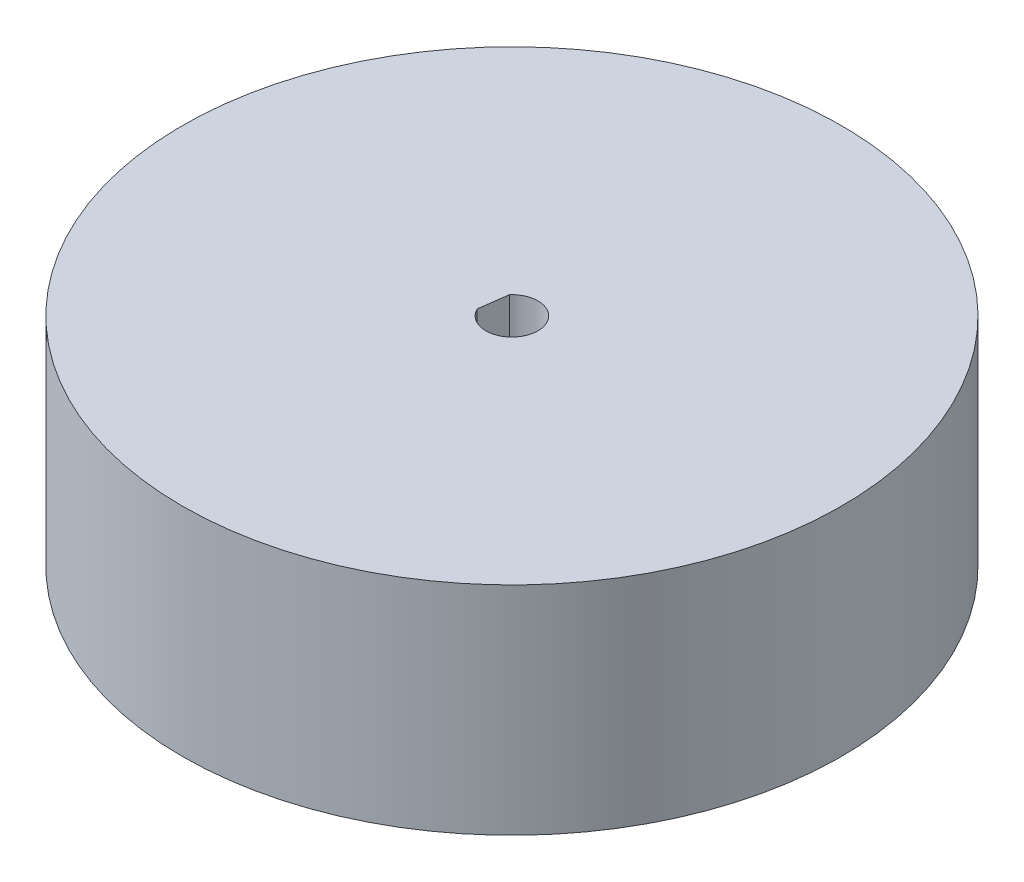
SolidWorks part; units mm, degrees
ref_plane "Front Plane" through (0, 0, 0) normal (0, 0, 1) x (1, 0, 0)
ref_plane "Top Plane" through (0, 0, 0) normal (0, 1, 0) x (1, 0, 0)
ref_plane "Right Plane" through (0, 0, 0) normal (1, 0, 0) x (0, 0, -1)
sketch "Sketch1" plane through (0, 0, 0) normal (0, 1, 0) x (1, 0, 0)
  circle A0 centre (0, 0) radius 38.0001
  dimension "D1" = 76.0001
extrude "Boss-Extrude1" add sketch "Sketch1" along normal blind 25
sketch "Sketch2" plane through (0, 25, 0) normal (0, 1, 0) x (1, 0, 0)
  point P1 (0, 0)
extrude "Cut-Extrude1" cut sketch "Sketch3" against normal blind 113.03 and the other way blind 126.238
sketch "Sketch3" plane through (-65.297, 25, 56.675) normal (0, 1, 0) x (-0.3903, 0, 0.9207)
  line L2 (-78.6089, 35.1526) -> (-75.408, 36.0229)
  circle A2 centre (-77.6643, 38) radius 38
  arc A4 (-75.408, 36.0229) -> (-78.6089, 35.1526) centre (-77.6643, 38) ccw
extrude "Cut-Extrude7" cut sketch "Sketch9" against normal through all
sketch "Sketch9" plane through (41.7415, -64.2886, -47.1561) normal (0, -1, 0) x (0.3713, 0, -0.9285)
  line L16 (-48.5036, -58.5074) -> (-44.2345, -61.2975)
  line L26 (-44.2345, -61.2975) -> (-34.9705, -47.123)
  line L32 (-25.7064, -32.9486) -> (-16.4424, -18.7741)
  line L33 (-16.4424, -18.7741) -> (-64.2813, 12.492)
  line L34 (-64.2813, 12.492) -> (-92.0733, -30.0315)
  line L35 (-92.0733, -30.0315) -> (-52.2704, -56.0455)
  line L42 (-25.3435, -23.0712) -> (-29.9755, -30.1584)
  line L50 (-52.2704, -56.0455) -> (-47.6982, -49.0497)
  line L52 (-34.9705, -47.123) -> (-43.0064, -41.871)
  line L57 (-29.1104, -20.6093) -> (-25.3435, -23.0712)
  line L58 (-43.0064, -41.871) -> (-29.1104, -20.6093)
  line L60 (-29.9755, -30.1584) -> (-25.7064, -32.9486)
  line L62 (-47.6982, -49.0497) -> (-43.9313, -51.5116)
  line L64 (-43.9313, -51.5116) -> (-48.5036, -58.5074)
  circle A1 centre (-59.2837, -21.2486) radius 17.8492
equation "\"MDF\"= 4.8mm"
equation "\"Foamcore\"= 4.6mm"
equation "\"GMaterial\"= \"MDF\""
equation "\"PCB\" = 1.6mm"
equation "\"BaseWidth\" = 10in"
equation "\"SkidLength\" = 1in"
equation "\"SkidClearance\" = 0.4in"
equation "\"MotorMountLength\" = 2in"
equation "\"MotorMountWidth\" = \"GMaterial\""
equation "\"MotorMountHeight\" = 2.25in"
equation "\"UnoStackWidth\" = 77.4mm"
equation "\"UnoStackLength\" = 79.8mm"
equation "\"UnoStackHeight\" = 34.2mm"
equation "\"TallHexRiserHeight\" = 22.2mm"
equation "\"PingPongBallSize\" = 40mm"
equation "\"BarrelLength\" = 9in"
equation "\"BarrelSize\" = \"PingPongBallSize\""
equation "\"PlatformLength\" = 4in"
equation "\"PlatformWidth\" = 6in"
equation "\"PitchingWheelWidth\" = 26.2mm"
equation "\"PitchingWheelDiameter\" = 65.5mm"
equation "\"ServoMountHeight\"=2.49223"
equation "\"ServoGearHeight\" = 0.95330261in"
equation "\"ServoMountLength\"= 1.53774"
equation "\"PivotHoleRadius\"= 0.616358"
equation "\"PlatformMountHeight\" = 3.19"
equation "\"TensionOffSet\"= .3mm"
equation "\"MotorMountWedge\"=0.333333"
equation "\"LaserCutterOffset\"= .3mm"
equation "\"BumperWidth\"=11"
equation "\"PitchingWheelMountOffset\" = 8.4mm"
equation "\"PitchingWheelInnerDiameter\" = 45.5mm"
equation "\"PitchingWheelBoltShoulder\" = 4.5mm"
equation "\"BrassCouplingLength\" = 18mm"
equation "\"PitcherWheelCompression\" = 2.5mm"
equation "\"PitchingMotorHeight\" = 57.0mm"
equation "\"PitchingMotorShaftTopHeight\" = \"PitchingMotorHeight\" - 44.1mm"
equation "\"PitchingMotorBodyHeight\" = 38mm"
equation "\"PitchingMotorTopShoulderHeight\" = 40.6mm - \"PitchingMotorBodyHeight\" "
equation "\"PitchingMotorBottomShoulderHeight\" = 40.2mm - \"PitchingMotorBodyHeight\""
equation "\"PitchingMotorBottomShaftHeight\" = \"PitchingMotorHeight\" - \"PitchingMotorShaftTopHeight\" - \"PitchingMotorTopShoulderHeight\" - \"PitchingMotorBodyHeight\" - \"PitchingMotorBottomShoulderHeight\""
equation "\"PitchingMotorShaftDiameter\" = 2.2mm"
equation "\"PitchingMotorBodyDiameter\" = 27.4mm"
equation "\"PitchingMotorTopShoulderDiameter\" = 9.8mm"
equation "\"PitchingMotorBottomShoulderDiameter\" = 9.8mm"
equation "\"BrassCouplingHexSize\" = 12mm"
equation "\"BrassCouplingBoreSize\" = 3.17mm"
equation "\"PitchingMotorMountingHoleDistance\" = 16mm"
equation "\"WheelWidth\"= 26mm"
equation "\"WheelDiameter\"=2.99213"
equation "\"ServoMountReductionBackHeight\"=2.25"
equation "\"Acrylic\" = 4.4mm"
equation "\"PitchingMotorDistance\" = \"PitchingWheelDiameter\" + \"PingPongBallSize\" - \"PitcherWheelCompression\"*2"
equation "\"PitchingMotorPlatformOffset\"=1"
equation "\"ServoPlatformOffset\"=1.64173"
equation "\"BallBearingDiameter\" = 22mm"
equation "\"BallBearingWidth\" = 9mm"
equation "\"BallBearingHexShoulder\" = 9mm - 5.9mm"
equation "\"BallBearingHexSize\" = .36in"
equation "\"D1@Sketch1\"=\"WheelDiameter\""
